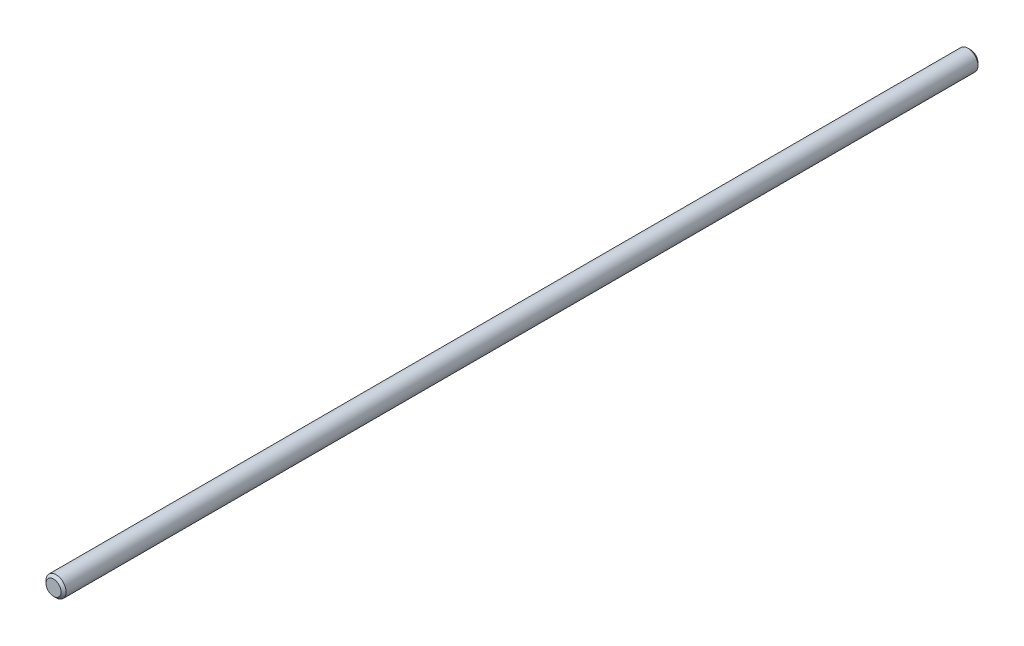
SolidWorks part; units mm, degrees
ref_plane "Front" through (0, 0, 0) normal (0, 0, 1) x (1, 0, 0)
ref_plane "Top" through (0, 0, 0) normal (0, 1, 0) x (1, 0, 0)
ref_plane "Right" through (0, 0, 0) normal (1, 0, 0) x (0, 0, -1)
sketch "Sketch1" plane through (0, 0, 0) normal (0, 0, 1) x (1, 0, 0)
  circle A0 centre (0, 0) radius 4
  dimension "D1" = 8
extrude "Boss-Extrude1" add sketch "Sketch1" along normal blind 365
chamfer "Chamfer1" distance 1 angle 45 2 edges at (4, 0, 365) (4, 0, 0)
